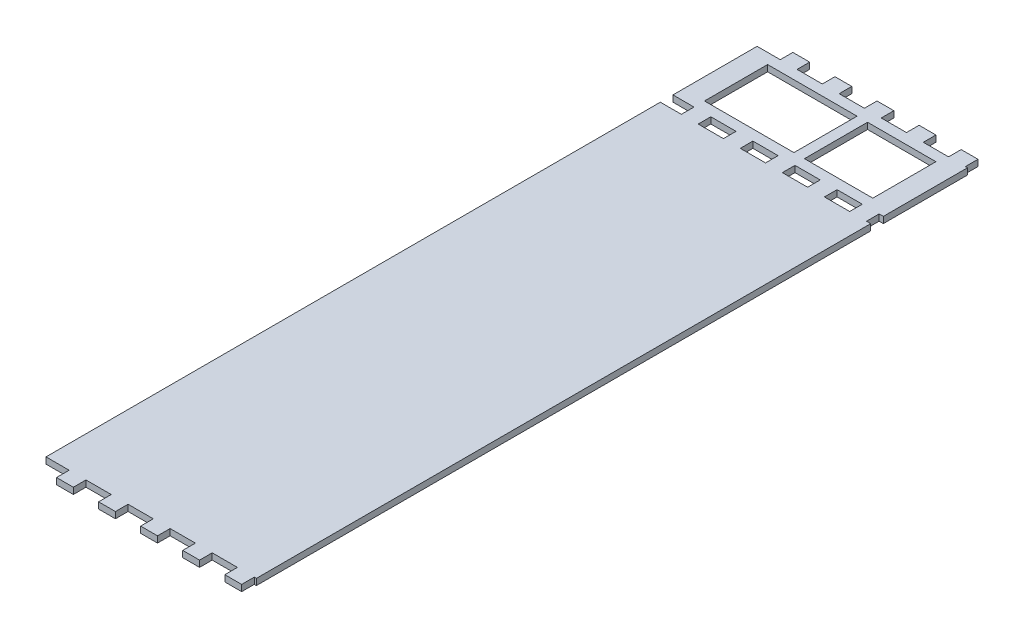
SolidWorks part; units mm, degrees
ref_plane "Plan de face" through (0, 0, 0) normal (0, 0, 1) x (1, 0, 0)
ref_plane "Plan de dessus" through (0, 0, 0) normal (0, 1, 0) x (1, 0, 0)
ref_plane "Plan de droite" through (0, 0, 0) normal (1, 0, 0) x (0, 0, -1)
sketch "Esquisse1" plane through (0, 0, 0) normal (0, 0, 1) x (1, 0, 0)
  line L1 (0, 0) -> (100, 0)
  line L2 (0, 0) -> (0, 3)
  line L3 (0, 3) -> (100, 3)
  line L4 (100, 0) -> (100, 3)
  dimension "D1" = 3
  dimension "D2" = 100
extrude "Boss.-Extru.1" add sketch "Esquisse1" along normal blind 338
sketch "Esquisse2" plane through (0, 0, 0) normal (0, -1, 0) x (1, 0, 0)
  line L0 (98, 40) -> (90, 40)
  line L1 (98, 40) -> (98, 46)
  line L2 (98, 46) -> (90, 46)
  line L3 (90, 40) -> (90, 46)
  line L4 (78, 40) -> (70, 40)
  line L5 (78, 40) -> (78, 46)
  line L6 (78, 46) -> (70, 46)
  line L7 (70, 40) -> (70, 46)
  line L8 (58, 40) -> (50, 40)
  line L9 (58, 40) -> (58, 46)
  line L10 (58, 46) -> (50, 46)
  line L11 (50, 40) -> (50, 46)
  line L12 (38, 40) -> (30, 40)
  line L13 (38, 40) -> (38, 46)
  line L14 (38, 46) -> (30, 46)
  line L15 (30, 40) -> (30, 46)
  line L16 (18, 40) -> (10, 40)
  line L17 (18, 40) -> (18, 46)
  line L18 (18, 46) -> (10, 46)
  line L19 (10, 40) -> (10, 46)
  line L20 (0, 338) -> (0, 0) construction
  line L21 (0, 0) -> (100, 0) construction
  line L22 (0, 46) -> (100, 46)
  line L23 (100, 338) -> (100, 0) construction
  line L24 (100, 46) -> (100, 40)
  line L25 (100, 40) -> (0, 40)
  line L26 (0, 40) -> (0, 46)
  line M2 (100, 0) -> (100, 338)
  line M4 (0, 338) -> (0, 0)
  dimension "D1" = 12
  dimension "D2" = 12
  dimension "D3" = 12
  dimension "D4" = 12
  dimension "D5" = 10
  dimension "D6" = 6
  dimension "D7" = 8
  dimension "D8" = 40
extrude "Enlèv. mat.-Extru.1" cut sketch "Esquisse2" against normal blind 6 contours L25 L11 L22 L13 | L25 L15 L22 L17 | L25 L7 L22 L9 | L25 L3 L22 L5 | L25 L22 L1 M2 | L25 L19 L22 M4
ref_plane "Plan1" through (0, 0, 169) normal (0, 0, -1) x (-1, 0, 0)
sketch "Esquisse3" plane through (0, 0, 0) normal (0, 0, -1) x (-1, 0, 0)
  line L0 (0, 0) -> (-100, 0) construction
  line L1 (-11, 0) -> (-19, 0)
  line L2 (-11, 0) -> (-11, 3)
  line L3 (-11, 3) -> (-19, 3)
  line L4 (-19, 0) -> (-19, 3)
  line L5 (-100, 3) -> (0, 3) construction
  line L6 (-31, 0) -> (-39, 0)
  line L7 (-31, 0) -> (-31, 3)
  line L8 (-31, 3) -> (-39, 3)
  line L9 (-39, 0) -> (-39, 3)
  line L10 (-51, 0) -> (-59, 0)
  line L11 (-51, 0) -> (-51, 3)
  line L12 (-51, 3) -> (-59, 3)
  line L13 (-59, 0) -> (-59, 3)
  line L14 (-71, 0) -> (-79, 0)
  line L15 (-71, 0) -> (-71, 3)
  line L16 (-71, 3) -> (-79, 3)
  line L17 (-79, 0) -> (-79, 3)
  line L18 (-91, 0) -> (-99, 0)
  line L19 (-91, 0) -> (-91, 3)
  line L20 (-91, 3) -> (-99, 3)
  line L21 (-99, 0) -> (-99, 3)
  line L22 (0, 3) -> (0, 0) construction
  dimension "D1" = 8
  dimension "D2" = 5
  dimension "D3" = 11
extrude "Boss.-Extru.2" add sketch "Esquisse3" along normal blind 6
mirror "Symétrie1" about plane through (0, 0, 169) normal (0, 0, -1) of "Boss.-Extru.2"
sketch "Esquisse4" plane through (0, 0, 0) normal (0, -1, 0) x (1, 0, 0)
  line L0 (0, 0) -> (11, 0) construction
  line L1 (10, 35) -> (90, 35)
  line L2 (10, 35) -> (10, 5)
  line L3 (10, 5) -> (90, 5)
  line L4 (90, 35) -> (90, 5)
  line L5 (10, 40) -> (0, 40) construction
  line L6 (0, 40) -> (0, 0) construction
  line L7 (100, 40) -> (100, 0) construction
  line L8 (59, -6) -> (51, -6) construction
  line L9 (52.5, 35) -> (57.5, 35)
  line L10 (52.5, 35) -> (52.5, 5)
  line L11 (52.5, 5) -> (57.5, 5)
  line L12 (57.5, 35) -> (57.5, 5)
  point P8 (0, 20)
  point P11 (100, 20)
  point P22 (55, -6)
  dimension "D1" = 5
  dimension "D2" = 5
  dimension "D3" = 10
  dimension "D4" = 10
  dimension "D5" = 5
  dimension "D6" = 2.5
extrude "Enlèv. mat.-Extru.2" cut sketch "Esquisse4" against normal blind 10 contours L10 L1 L2 L3 | L1 L12 L3 L4
